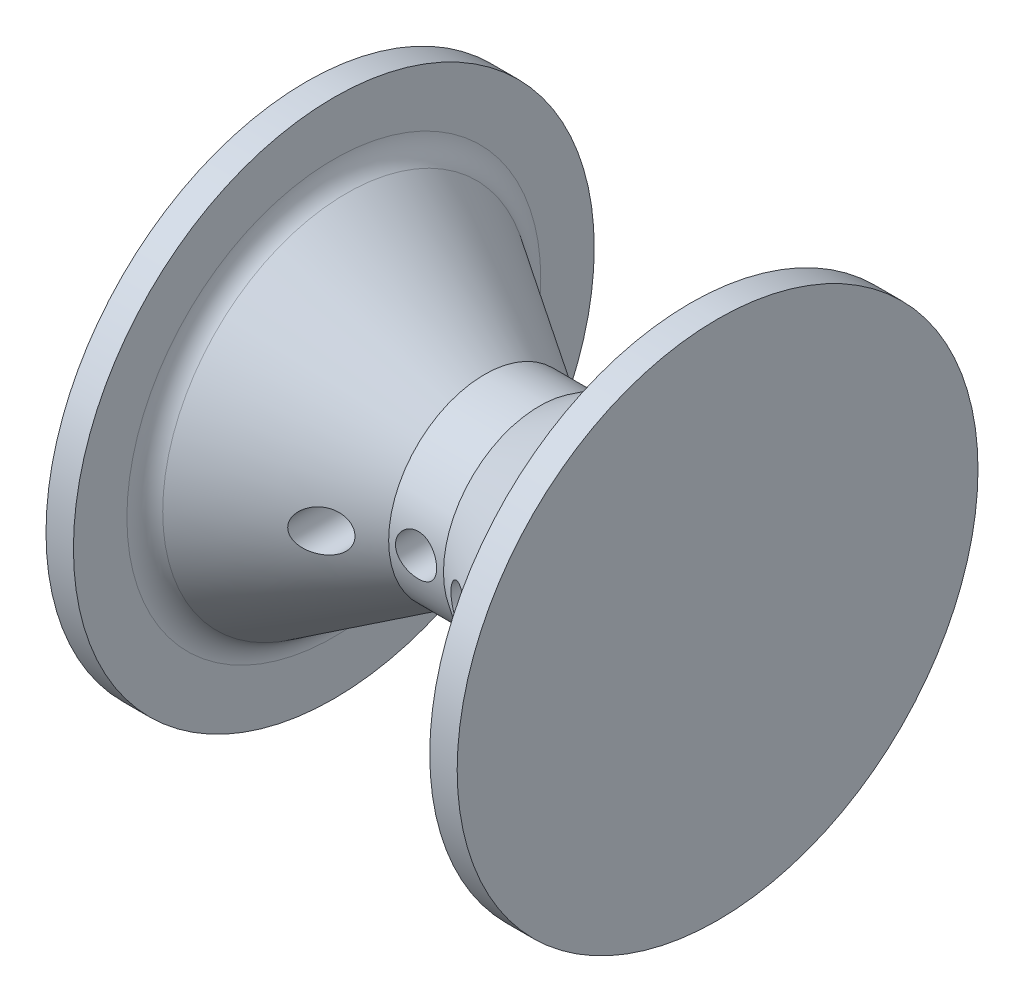
SolidWorks part; units mm, degrees
ref_plane "Front Plane" through (0, 0, 0) normal (0, 0, 1) x (1, 0, 0)
ref_plane "Top Plane" through (0, 0, 0) normal (0, 1, 0) x (1, 0, 0)
ref_plane "Right Plane" through (0, 0, 0) normal (1, 0, 0) x (0, 0, -1)
sketch "Sketch2" plane through (0, 0, 0) normal (0, 0, 1) x (1, 0, 0)
  line L0 (0, 0) -> (23.9161, 0) construction
  line L2 (0, 0) -> (0, 13.1643) construction
  line L3 (13, 14) -> (13, 19)
  line L4 (13, 19) -> (15, 19)
  line L5 (15, 19) -> (15, 0)
  line L6 (-2, 7) -> (2, 7)
  line L7 (2, 7) -> (13, 14)
  line L8 (-2, 7) -> (-13, 14)
  line L9 (-15, 19) -> (-15, 0)
  line L10 (-13, 19) -> (-15, 19)
  line L11 (-13, 14) -> (-13, 19)
  line L12 (-15, 0) -> (15, 0)
  dimension "D1" = 15
  dimension "D2" = 19
  dimension "D3" = 5
  dimension "D4" = 2
  dimension "D5" = 2
  dimension "D6" = 7
revolve "Revolve1" add sketch "Sketch2" angle 360 about L0
sketch "Sketch3" plane through (-15, 0, 0) normal (-1, 0, 0) x (0, 0, 1)
  line L0 (2.9, 1.5748) -> (2.9, -1.5748)
  arc A0 (2.9, 1.5748) -> (2.9, -1.5748) centre (0, 0) ccw
extrude "motor shaft" cut sketch "Sketch3" against normal blind 13
sketch "Sketch4" plane through (0, 0, 0) normal (0, 0, 1) x (1, 0, 0)
  circle A0 centre (0, 0) radius 1.5
  circle A1 centre (5, 0) radius 1.5
  circle A2 centre (-5, 0) radius 1.5
  dimension "D1" = 3
  dimension "D2" = 2
  dimension "D3" = 2
extrude "Cut-Extrude2" cut sketch "Sketch4" against normal mid plane 35
fillet "Fillet1" radius 2 2 edges at (-13, 0, 14) (13, 0, 14)
